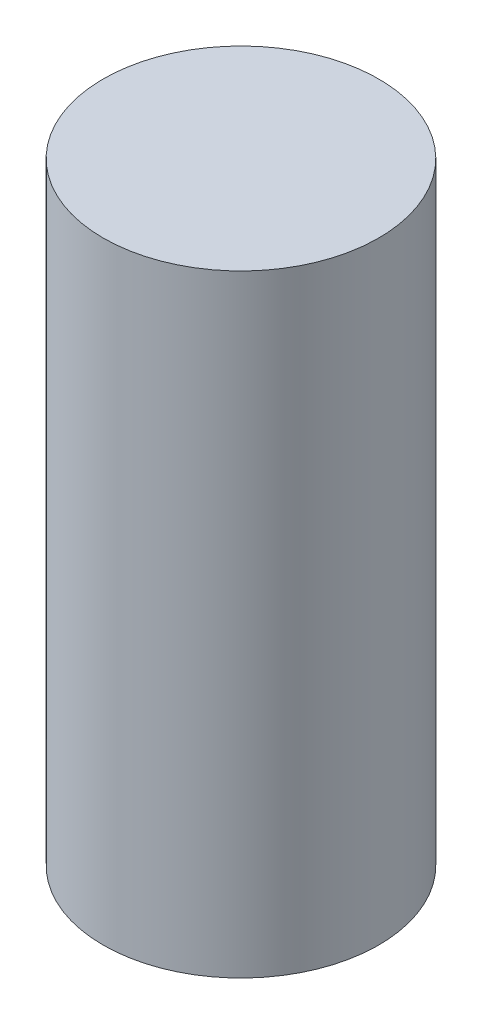
SolidWorks part; units mm, degrees
ref_plane "Front Plane" through (0, 0, 0) normal (0, 0, 1) x (1, 0, 0)
ref_plane "Top Plane" through (0, 0, 0) normal (0, 1, 0) x (1, 0, 0)
ref_plane "Right Plane" through (0, 0, 0) normal (1, 0, 0) x (0, 0, -1)
sketch "Sketch1" plane through (0, 0, 0) normal (0, 1, 0) x (1, 0, 0)
  circle A0 centre (0, 0) radius 4.95
extrude "Boss-Extrude1" add sketch "Sketch1" along normal blind 22
